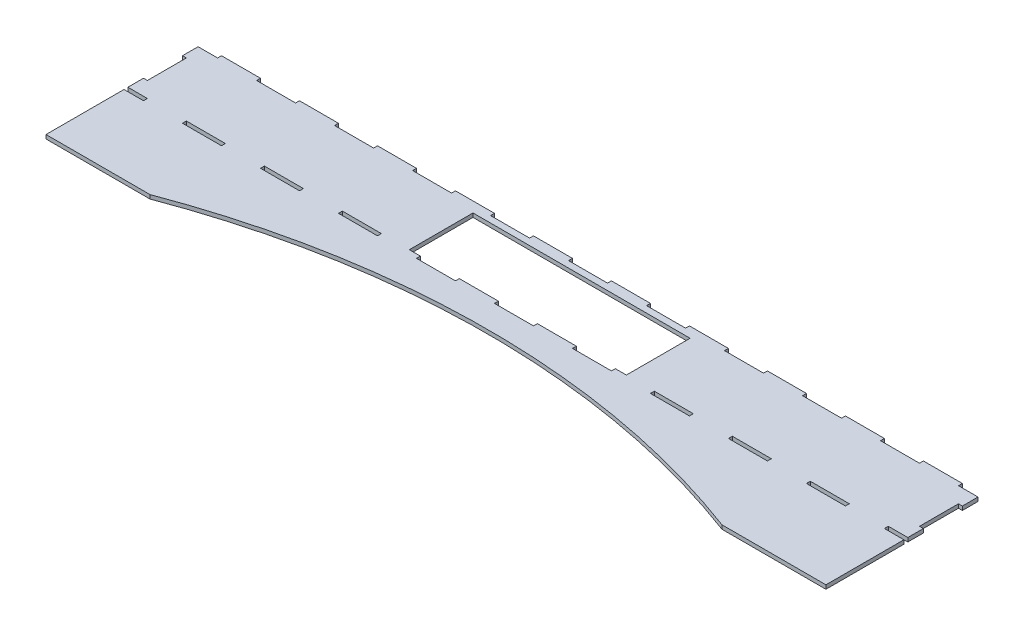
SolidWorks part; units mm, degrees
ref_plane "Front Plane" through (0, 0, 0) normal (0, 0, 1) x (1, 0, 0)
ref_plane "Top Plane" through (0, 0, 0) normal (0, 1, 0) x (1, 0, 0)
ref_plane "Right Plane" through (0, 0, 0) normal (1, 0, 0) x (0, 0, -1)
sketch "Sketch1" plane through (0, 0, 0) normal (0, 1, 0) x (1, 0, 0)
  line L1 (0, 0) -> (600, 0)
  line L2 (0, 0) -> (0, 60)
  line L3 (0, 60) -> (600, 60)
  line L4 (600, 0) -> (600, 60)
  dimension "D1" = 600
  dimension "D2" = 60
extrude "Boss-Extrude1" add sketch "Sketch1" along normal blind 3
sketch "Sketch4" plane through (0, 3, 0) normal (0, 1, 0) x (1, 0, 0)
  line L0 (600, 0) -> (600, 60) construction
  line L1 (0, 0) -> (600, 0)
  line L2 (0, 0) -> (0, -60)
  line L3 (0, -60) -> (600, -60)
  line L4 (600, 0) -> (600, -60)
  line L5 (0, 0) -> (600, 0) construction
  dimension "D1" = 60
extrude "Boss-Extrude4" add sketch "Sketch4" against normal blind 3
sketch "Sketch2" plane through (0, 3, 0) normal (0, 1, 0) x (1, 0, 0)
  line L0 (300, 57) -> (300, 3) construction
  line L1 (-15, 0) -> (15, 0)
  line L2 (-15, 0) -> (-15, 3)
  line L3 (-15, 3) -> (15, 3)
  line L4 (15, 0) -> (15, 3)
  line L5 (0, 60) -> (0, -60) construction
  line L6 (45, 0) -> (45, 3)
  line L7 (45, 0) -> (75, 0)
  line L8 (75, 0) -> (75, 3)
  line L9 (45, 3) -> (75, 3)
  line L10 (105, 0) -> (105, 3)
  line L11 (105, 0) -> (135, 0)
  line L12 (135, 0) -> (135, 3)
  line L13 (105, 3) -> (135, 3)
  line L14 (165, 0) -> (165, 3)
  line L15 (165, 0) -> (195, 0)
  line L16 (195, 0) -> (195, 3)
  line L17 (165, 3) -> (195, 3)
  line L18 (225, 0) -> (225, 3)
  line L19 (225, 0) -> (255, 0)
  line L20 (255, 0) -> (255, 3)
  line L21 (225, 3) -> (255, 3)
  line L22 (285, 0) -> (285, 3)
  line L23 (285, 0) -> (315, 0)
  line L24 (315, 0) -> (315, 3)
  line L25 (285, 3) -> (315, 3)
  line L26 (345, 0) -> (345, 3)
  line L27 (345, 0) -> (375, 0)
  line L28 (375, 0) -> (375, 3)
  line L29 (345, 3) -> (375, 3)
  line L30 (405, 0) -> (405, 3)
  line L31 (405, 0) -> (435, 0)
  line L32 (435, 0) -> (435, 3)
  line L33 (405, 3) -> (435, 3)
  line L34 (465, 0) -> (465, 3)
  line L35 (465, 0) -> (495, 0)
  line L36 (495, 0) -> (495, 3)
  line L37 (465, 3) -> (495, 3)
  line L38 (525, 0) -> (525, 3)
  line L39 (525, 0) -> (555, 0)
  line L40 (555, 0) -> (555, 3)
  line L41 (525, 3) -> (555, 3)
  line L42 (0, 30) -> (600, 30) construction
  line L43 (600, 15) -> (597, 15)
  line L44 (525, 57) -> (555, 57)
  line L45 (555, 60) -> (555, 57)
  line L46 (525, 60) -> (555, 60)
  line L47 (525, 60) -> (525, 57)
  line L48 (465, 57) -> (495, 57)
  line L49 (495, 60) -> (495, 57)
  line L50 (465, 60) -> (495, 60)
  line L51 (465, 60) -> (465, 57)
  line L52 (405, 57) -> (435, 57)
  line L53 (435, 60) -> (435, 57)
  line L54 (405, 60) -> (435, 60)
  line L55 (405, 60) -> (405, 57)
  line L56 (345, 57) -> (375, 57)
  line L57 (375, 60) -> (375, 57)
  line L58 (345, 60) -> (375, 60)
  line L59 (345, 60) -> (345, 57)
  line L60 (285, 57) -> (315, 57)
  line L61 (315, 60) -> (315, 57)
  line L62 (285, 60) -> (315, 60)
  line L63 (285, 60) -> (285, 57)
  line L64 (225, 57) -> (255, 57)
  line L65 (255, 60) -> (255, 57)
  line L66 (225, 60) -> (255, 60)
  line L67 (225, 60) -> (225, 57)
  line L68 (165, 57) -> (195, 57)
  line L69 (195, 60) -> (195, 57)
  line L70 (165, 60) -> (195, 60)
  line L71 (165, 60) -> (165, 57)
  line L72 (105, 57) -> (135, 57)
  line L73 (135, 60) -> (135, 57)
  line L74 (105, 60) -> (135, 60)
  line L75 (105, 60) -> (105, 57)
  line L76 (45, 57) -> (75, 57)
  line L77 (75, 60) -> (75, 57)
  line L78 (45, 60) -> (75, 60)
  line L79 (45, 60) -> (45, 57)
  line L80 (15, 60) -> (15, 57)
  line L81 (-15, 57) -> (15, 57)
  line L82 (-15, 60) -> (-15, 57)
  line L83 (-15, 60) -> (15, 60)
  line L84 (600, 60) -> (0, 60) construction
  line L85 (0, 45) -> (3, 45)
  line L86 (0, 45) -> (0, 15)
  line L87 (0, 15) -> (3, 15)
  line L88 (3, 45) -> (3, 15)
  line L89 (597, 45) -> (597, 15)
  line L94 (585, 0) -> (585, 3)
  line L99 (585, 0) -> (615, 0)
  line L100 (615, 0) -> (615, 3)
  line L101 (585, 3) -> (615, 3)
  line L102 (585, 60) -> (615, 60)
  line L103 (615, 60) -> (615, 57)
  line L104 (585, 57) -> (615, 57)
  line L105 (585, 60) -> (585, 57)
  line L106 (600, 45) -> (597, 45)
  line L107 (600, 45) -> (600, 15)
  point P96 (600, 30)
  point P97 (0, 0)
  dimension "D1" = 30
  dimension "D2" = 15
  dimension "D3" = 3
  dimension "D5" = 15
  dimension "D6" = 30
  dimension "D4" = 11
extrude "Cut-Extrude1" cut sketch "Sketch2" against normal blind 5
sketch "Sketch5" plane through (0, 3, 0) normal (0, 1, 0) x (1, 0, 0)
  line L0 (435, 3) -> (405, 3) construction
  line L5 (285, 57) -> (315, 57) construction
  line L7 (345, 57) -> (375, 57) construction
  line L14 (216.5, 52) -> (383.5, 52)
  line L15 (216.5, 52) -> (216.5, 3)
  line L16 (216.5, 3) -> (383.5, 3)
  line L17 (383.5, 52) -> (383.5, 3)
  point P7 (300, 52)
  point P12 (300, 57)
  dimension "D1" = 167
  dimension "D2" = 5
extrude "Cut-Extrude2" cut sketch "Sketch5" against normal blind 5
sketch "Sketch6" plane through (0, 3, 0) normal (0, 1, 0) x (1, 0, 0)
  line L0 (0, -60) -> (600, -60) construction
  line L2 (80, -60) -> (520, -60)
  arc A0 (80, -60) -> (520, -60) centre (300, -645) cw
  point P3 (300, -20)
  dimension "D1" = 80
  dimension "D2" = 80
  dimension "D3" = 40
extrude "Cut-Extrude3" cut sketch "Sketch6" against normal blind 5
